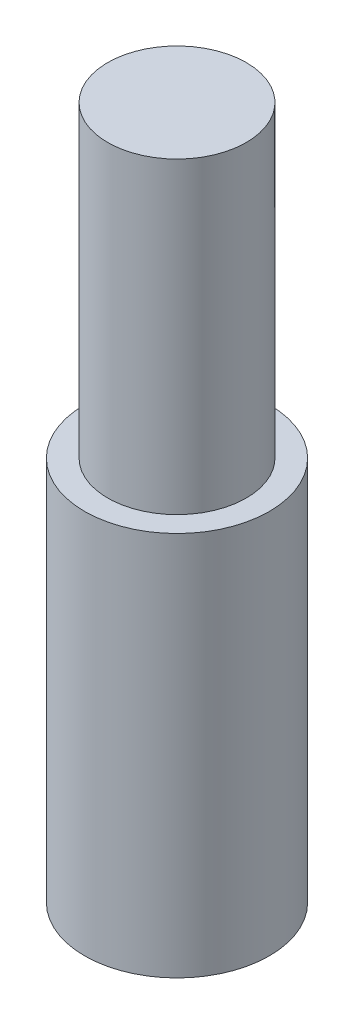
SolidWorks part; units mm, degrees
ref_plane "Ebene vorne" through (0, 0, 0) normal (0, 0, 1) x (1, 0, 0)
ref_plane "Ebene oben" through (0, 0, 0) normal (0, 1, 0) x (1, 0, 0)
ref_plane "Ebene rechts" through (0, 0, 0) normal (1, 0, 0) x (0, 0, -1)
sketch "Skizze1" plane through (0, 0, 0) normal (0, 0, 1) x (1, 0, 0)
  line L0 (0, 45) -> (0, 0)
  line L3 (0, 45) -> (4.5, 45)
  line L4 (4.5, 45) -> (4.5, 25)
  line L5 (4.5, 25) -> (6, 25)
  line L6 (6, 25) -> (6, 0)
  line L7 (6, 0) -> (0, 0)
  line L8 (0, -3.346) -> (0, 54.7199) construction
  dimension "D1" = 6
  dimension "D2" = 20
  dimension "D3" = 25
  dimension "D4" = 4.5
revolve "Rotation3" add sketch "Skizze1" angle 360 about L8
